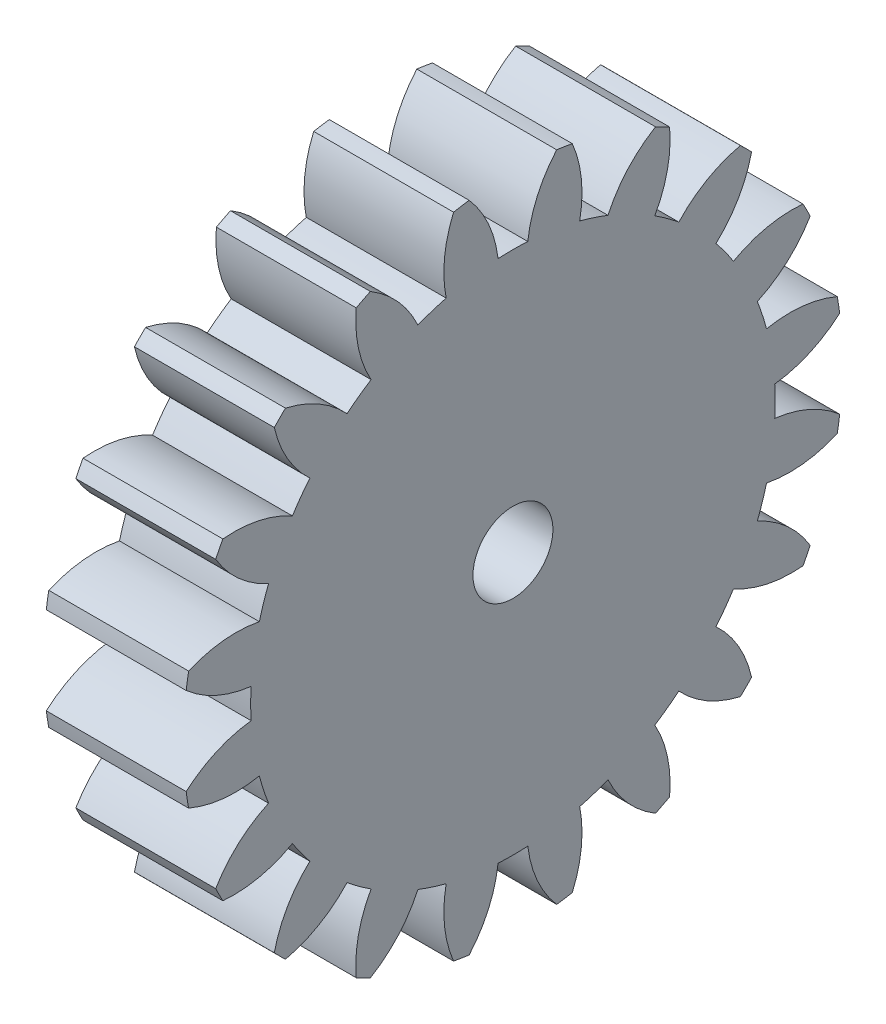
SolidWorks part; units mm, degrees
ref_plane "Plane1" through (0, 0, 0) normal (0, 0, 1) x (1, 0, 0)
ref_plane "Plane2" through (0, 0, 0) normal (0, 1, 0) x (1, 0, 0)
ref_plane "Plane3" through (0, 0, 0) normal (1, 0, 0) x (0, 0, -1)
other "Configuration Table"
sketch "HoldingSke" plane through (0, 0, 0) normal (0, 1, 0) x (1, 0, 0)
  line L0 (0, 0) -> (0.6265, -0.228)
  line L1 (-15, 0) -> (100, 0) construction
  line L2 (0, 0) -> (-2.1039, 2.3779)
  line L3 (0, 0) -> (-11.863, 4.5341)
  line L4 (0, 0) -> (8.1152, 2.9537)
  line L5 (0, 0) -> (-46.8476, -17.4728)
  line L6 (0, 0) -> (-5.8027, -3.9151)
  line L7 (-2.1039, 2.3779) -> (8.6586, 51.2059)
  line L8 (-76.2, 54.61) -> (-75.5, 54.61)
  line L9 (-71.009, 38.7566) -> (-53.1078, 45.2721)
  line L10 (-76.2, 71.12) -> (104.1128, 71.12)
  line L11 (0, 0) -> (-7, 0)
  line L12 (-76.2, 101.6) -> (-76.147, 101.6)
  line L13 (24.9733, 27.94) -> (52.9518, 28.4284)
  line L14 (24.9733, 27.94) -> (24.9743, 27.94)
  line L15 (24.9733, 27.94) -> (100.4006, 29.5858)
  line L16 (-63.627, -1.5) -> (-12.827, -1.5)
  circle A0 centre (0, 0) radius 2
  circle A1 centre (0, 0) radius 13.124
  circle A2 centre (0, 0) radius 37.5
  circle A3 centre (0, 0) radius 2
  dimension "MHD" = 26.248
  dimension "Hub_dia" = 75
  dimension "Bore" = 4
  dimension "MBD" = 4
  dimension "Num_teeth" = 20
  dimension "Pitch" = 0.6667
  dimension "Overall_len" = 50
  dimension "Show_teeth" = 20
  dimension "Thickness" = 7
  dimension "OAL" = 50.0001
  dimension "T_dim" = 0.7
  dimension "Ap" = 20
  dimension "H" = 19.05
  dimension "Pitch_radius" = 180.3128
  dimension "Width" = 7
  dimension "Backlash" = 0.053
  dimension "Addendum_fac" = 1
  dimension "Dedendum_fac" = 1.25
  dimension "Clearance_fac" = 0.25
  dimension "Dedendum_add" = 0.001
  dimension "Module" = 1.5
sketch "BasProSke" plane through (0, 0, 0) normal (0, 1, 0) x (1, 0, 0)
  line L0 (-10, 0) -> (60, 0) construction
  line L1 (0, 0) -> (0, 16.5)
  line L2 (0, 0) -> (7, 0)
  line L3 (7, 0) -> (7, 16.5)
  line L4 (7, 16.5) -> (0, 16.5)
  dimension "Thickness" = 7
  dimension "Diameter" = 33
revolve "Base-Revolve" add sketch "BasProSke" angle 360 about L0
sketch "TooCutSke" plane through (0, 0, 0) normal (1, 0, 0) x (0, 0, -1)
  line L1 (0, 0) -> (0, 107) construction
  line L2 (0, 0) -> (-1.2696, 14.9462) construction
  line L3 (0, 0) -> (-4.6808, 29.5532) construction
  line L4 (-1.2696, 14.9462) -> (-2.3404, 14.7766) construction
  arc A0 (0.7438, 13.1029) -> (-0.7438, 13.1029) centre (0, 0) ccw
  arc A1 (2.21, 16.377) -> (-2.21, 16.377) centre (0, 0) ccw
  circle A2 centre (0, 0) radius 15 construction
  circle A3 centre (0, 0) radius 14.0954 construction
  arc A4 (-0.7438, 13.1029) -> (-2.21, 16.377) centre (-6.7025, 12.3999) ccw
  arc A5 (2.21, 16.377) -> (0.7438, 13.1029) centre (6.7025, 12.3999) ccw
  dimension "Root_dia" = 26.248
  dimension "Overcut_dia" = 33.0508
  dimension "Pitch_dia" = 30
  dimension "Base_dia" = 28.1908
  dimension "Flank_rad" = 6
  dimension "Half_ang" = 9
  dimension "Half_CT" = 1.0841
extrude "ToothCut" cut sketch "TooCutSke" along normal through all
fillet "Breaks" [suppressed] radius 0.03
fillet "RootFillets" [suppressed] radius 0.376
pattern_circular "TeethCuts" count 20 every 18 about axis through (-10, 0, 0) along (1, 0, 0) of "ToothCut", "RootFillets", "Breaks"
sketch "HubNeaOneSke" plane through (0, 0, 0) normal (-1, 0, 0) x (0, 0, 1)
  circle A0 centre (0, 0) radius 13.124
  dimension "Diameter" = 26.248
extrude "HubNearOne" [suppressed] add sketch "HubNeaOneSke" along normal blind 43.0001
sketch "HubNeaBotSke" plane through (0, 0, 0) normal (-1, 0, 0) x (0, 0, 1)
  circle A0 centre (0, 0) radius 13.124
  dimension "Diameter" = 26.248
extrude "HubNearBoth" [suppressed] add sketch "HubNeaBotSke" along normal blind 21.5
ref_plane "FarPln" through (7, 0, 0) normal (1, 0, 0) x (0, 0, -1)
sketch "HubFarSke" plane through (7, 0, 0) normal (1, 0, 0) x (0, 0, -1)
  circle A0 centre (0, 0) radius 13.124
  dimension "Diameter" = 26.248
extrude "HubFar" [suppressed] add sketch "HubFarSke" along normal blind 21.5
sketch "BorSke" plane through (0, 0, 0) normal (1, 0, 0) x (0, 0, -1)
  circle A0 centre (0, 0) radius 2
  dimension "Diameter" = 4
extrude "Bore" cut sketch "BorSke" along normal mid plane 100.0001
sketch "KeySke" plane through (0, 0, 0) normal (1, 0, 0) x (0, 0, -1)
  line L0 (-0.8, 0) -> (-0.8, 2.7)
  line L1 (-0.8, 2.7) -> (0.8, 2.7)
  line L2 (0.8, 2.7) -> (0.8, 0)
  line L3 (0, 0) -> (0, 34) construction
  line L4 (-0.8, 0) -> (0.8, 0)
  dimension "Offset" = 2.7
  dimension "Width" = 1.6
extrude "Keyway" [suppressed] cut sketch "KeySke" along normal mid plane 100.0001
pattern_circular "Keyway2" [suppressed] count 2 every 90 about axis through (-10, 0, 0) along (1, 0, 0)
equation "' \"Module@HoldingSke\" = 6.35"
equation "' \"Num_teeth@HoldingSke\" = 12"
equation "' \"Ap@HoldingSke\" =  20"
equation "' \"Ap@HoldingSke\" = 20"
equation "' \"Width@HoldingSke\" = 0.5 * 25.4"
equation "' \"Hub_dia@HoldingSke\"= 1 * 25.4"
equation "' \"Hub_dia@HoldingSke\" = 1 * 25.4"
equation "' \"Overall_len@HoldingSke\" = 1.0 * 25.4"
equation "' \"Bore@HoldingSke\" = 0.75 * 25.4"
equation "' \"T_dim@HoldingSke\" = 0.1 * 25.4"
equation "' \"Width@KeySke\" = 0.25 * 25.4"
equation "' \"Show_teeth@HoldingSke\" = 13"
equation "' \"Backlash@HoldingSke\" = 0.009 * 25.4"
equation "' \"Addendum_fac@HoldingSke\" = 1.0"
equation "' \"Dedendum_fac@HoldingSke\" = 1.25"
equation "' \"Dedendum_add@HoldingSke\" = 0.00005 * 25.4"
equation "' \"Clearance_fac@HoldingSke\" = 0.25"
equation "\"Pitch@HoldingSke\" = 1 / \"Module@HoldingSke\""
equation "\"Overcut_dia@TooCutSke\" = (\"Num_teeth@HoldingSke\" + 2 * \"Addendum_fac@HoldingSke\") / \"Pitch@HoldingSke\" + 0.002 * 25.4"
equation "\"Pitch_dia@TooCutSke\" = \"Num_teeth@HoldingSke\" / \"Pitch@HoldingSke\""
equation "\"Base_dia@TooCutSke\" = \"Num_teeth@HoldingSke\" / \"Pitch@HoldingSke\" * cos((\"Ap@HoldingSke\"  * 3.14159265 / 180))"
equation "\"Root_dia@TooCutSke\" = (\"Num_teeth@HoldingSke\" + 2) / \"Pitch@HoldingSke\" - 2 * (\"Addendum_fac@HoldingSke\" + \"Dedendum_fac@HoldingSke\") / \"Pitch@HoldingSke\" - \"Dedendum_add@HoldingSke\" * 2"
equation "\"Half_ang@TooCutSke\" = 180 / \"Num_teeth@HoldingSke\""
equation "\"Half_CT@TooCutSke\" = \"Num_teeth@HoldingSke\" / \"Pitch@HoldingSke\" * sin((3.14159265 / 2 / \"Num_teeth@HoldingSke\")) / 2 - 7 * \"Backlash@HoldingSke\" / 4"
equation "\"Flank_rad@TooCutSke\" = \"Num_teeth@HoldingSke\" / \"Pitch@HoldingSke\" / 5"
equation "\"Radius@RootFillets\" = \"Clearance_fac@HoldingSke\" / \"Pitch@HoldingSke\" + \"Dedendum_add@HoldingSke\""
equation "\"Break_rad@Breaks\" = 0.02 / \"Pitch@HoldingSke\""
equation "\"Thickness@HoldingSke\" = \"Width@HoldingSke\""
equation "\"OAL@HoldingSke\" = \"Thickness@HoldingSke\""
equation "\"MHD@HoldingSke\" = (\"Num_teeth@HoldingSke\" + 2) / \"Pitch@HoldingSke\" - 2 * (\"Addendum_fac@HoldingSke\" + \"Dedendum_fac@HoldingSke\")  / \"Pitch@HoldingSke\" - \"Dedendum_add@HoldingSke\" * 2"
equation "\"MBD@HoldingSke\" = (\"Num_teeth@HoldingSke\" + 2) / \"Pitch@HoldingSke\" - 2 * (\"Addendum_fac@HoldingSke\" + \"Dedendum_fac@HoldingSke\")  / \"Pitch@HoldingSke\" - \"Dedendum_add@HoldingSke\" * 2 - 0.002 * 25.4"
equation "\"MHD@HoldingSke\" = ((sgn( \"MHD@HoldingSke\" - \"Hub_dia@HoldingSke\" )-1)*( \"MHD@HoldingSke\" - \"Hub_dia@HoldingSke\" ))/-2+ \"Hub_dia@HoldingSke\""
equation "\"MBD@HoldingSke\" = ((sgn( \"MBD@HoldingSke\" - \"Bore@HoldingSke\" )-1)*( \"MBD@HoldingSke\" - \"Bore@HoldingSke\" ))/-2+ \"Bore@HoldingSke\""
equation "\"OAL@HoldingSke\" = ((sgn( \"OAL@HoldingSke\" - \"Overall_len@HoldingSke\" )+1)*( \"OAL@HoldingSke\" - \"Overall_len@HoldingSke\" ))/2 + \"Overall_len@HoldingSke\" + 0.000002 * 25.4"
equation "\"Num_teeth@TeethCuts\" = int( \"Show_teeth@HoldingSke\" ) + 1"
equation "\"Num_teeth@TeethCuts\" = ((sgn( \"Num_teeth@TeethCuts\" - \"Num_teeth@HoldingSke\" )-1)*( \"Num_teeth@TeethCuts\" - \"Num_teeth@HoldingSke\" ))/-2+ \"Num_teeth@HoldingSke\""
equation "\"Num_teeth@TeethCuts\" = ((sgn( \"Num_teeth@TeethCuts\" - 2.0)+1)*( \"Num_teeth@TeethCuts\" - 2.0))/2 +2.0"
equation "\"Angle@TeethCuts\" = 360.0 / \"Num_teeth@HoldingSke\""
equation "\"Diameter@BasProSke\" = (\"Num_teeth@HoldingSke\" + 2 * \"Addendum_fac@HoldingSke\") / \"Pitch@HoldingSke\""
equation "\"Thickness@BasProSke\"  = \"Thickness@HoldingSke\""
equation "' \"Fillet_rad@BasProSke\" =  \"Thickness@HoldingSke\" * 0.05"
equation "' \"Fillet_rad@BasProSke\" = \"Thickness@HoldingSke\" * 0.05"
equation "\"MHD@HoldingSke\" = ((sgn( \"MHD@HoldingSke\" - \"Root_dia@TooCutSke\" )-1)*( \"MHD@HoldingSke\" - \"Root_dia@TooCutSke\" ))/-2+ \"Root_dia@TooCutSke\""
equation "\"Diameter@HubNeaOneSke\" = \"MHD@HoldingSke\""
equation "\"Length@HubNearOne\" = \"OAL@HoldingSke\" - \"Thickness@BasProSke\""
equation "\"Diameter@HubNeaBotSke\" = \"MHD@HoldingSke\""
equation "\"Length@HubNearBoth\" = ( \"OAL@HoldingSke\" - \"Thickness@BasProSke\" ) / 2.0"
equation "\"Thickness@FarPln\" = \"Thickness@BasProSke\""
equation "\"Diameter@HubFarSke\" = \"MHD@HoldingSke\""
equation "\"Length@HubFar\" = ( \"OAL@HoldingSke\" - \"Thickness@BasProSke\" ) / 2.0"
equation "\"Diameter@BorSke\" = \"MBD@HoldingSke\""
equation "\"D1@Bore\" = \"OAL@HoldingSke\" * 2.0"
equation "\"D1@Keyway\" = \"OAL@HoldingSke\" * 2.0"
equation "\"Offset@KeySke\" = \"T_dim@HoldingSke\" + \"MBD@HoldingSke\" / 2.0"
